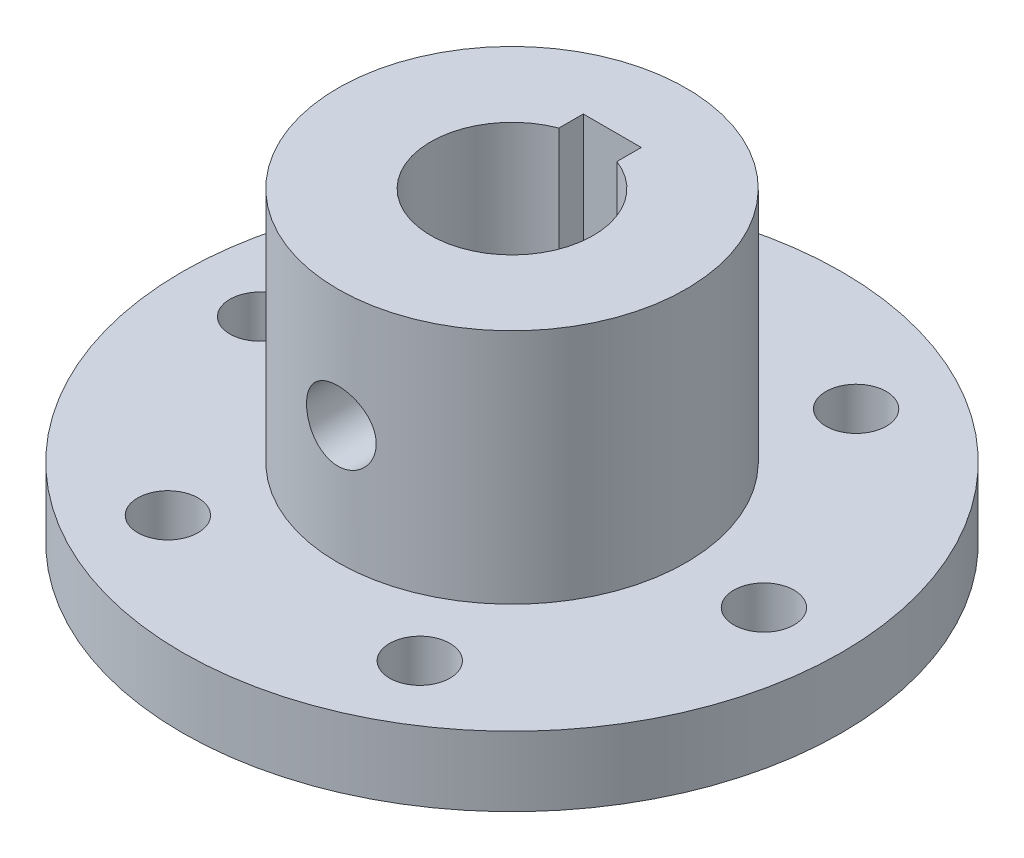
SolidWorks part; units mm, degrees
ref_plane "Front Plane" through (0, 0, 0) normal (0, 0, 1) x (1, 0, 0)
ref_plane "Top Plane" through (0, 0, 0) normal (0, 1, 0) x (1, 0, 0)
ref_plane "Right Plane" through (0, 0, 0) normal (1, 0, 0) x (0, 0, -1)
sketch "Sketch1" plane through (0, 0, 0) normal (0, 1, 0) x (1, 0, 0)
  circle A0 centre (0, 0) radius 28.4
  dimension "D1" = 56.8
extrude "Boss-Extrude1" add sketch "Sketch1" along normal blind 6
sketch "Sketch2" plane through (0, 6, 0) normal (0, 1, 0) x (1, 0, 0)
  circle A0 centre (0, 0) radius 15
  dimension "D1" = 30
extrude "Boss-Extrude2" add sketch "Sketch2" along normal blind 20.4
sketch "Sketch3" plane through (0, 26.4, 0) normal (0, 1, 0) x (1, 0, 0)
  line L1 (-2.5, 8.6383) -> (2.5, 8.6383)
  line L2 (-2.5, 8.6383) -> (-2.5, 6.5383)
  line L4 (2.5, 8.6383) -> (2.5, 6.5383)
  line L5 (-2.5, 8.6383) -> (2.5, 6.5383) construction
  line L6 (-2.5, 6.5383) -> (2.5, 8.6383) construction
  arc A0 (-2.5, 6.5383) -> (2.5, 6.5383) centre (0, 0) ccw
  point P7 (0, 7.5883)
  point P10 (0, 8.6383)
  dimension "D1" = 14
  dimension "D2" = 5
  dimension "D3" = 2.1
extrude "Cut-Extrude1" cut sketch "Sketch3" against normal through all
sketch "Sketch4" plane through (0, 0, 0) normal (0, 0, 1) x (1, 0, 0)
  line L0 (7, 26.4) -> (-7, 26.4) construction
  line L1 (0, 0) -> (0, 16.2) construction
  circle A0 centre (0, 16.2) radius 3
  dimension "D1" = 6
  dimension "D2" = 10.2
extrude "Cut-Extrude2" cut sketch "Sketch4" along normal through all
sketch "Sketch5" plane through (0, 6, 0) normal (0, 1, 0) x (1, 0, 0)
  line L0 (-21.7, 0) -> (-28.4, 0) construction
  line L1 (-21.7, 0) -> (-15, 0) construction
  line L2 (-21.7, 0) -> (-21.7, 18.3213) construction
  line L3 (-21.7, 0) -> (-21.7, -18.3213) construction
  circle A0 centre (-21.7, 0) radius 2.6
  circle A1 centre (0, 0) radius 28.4 construction
  circle A2 centre (0, 0) radius 15 construction
  dimension "D1" = 5.2
extrude "Cut-Extrude3" cut sketch "Sketch5" against normal through all
pattern_circular "CirPattern1" count 6 over 360 about axis through (0, 0, 0) along (0, 1, 0) of "Cut-Extrude3"
